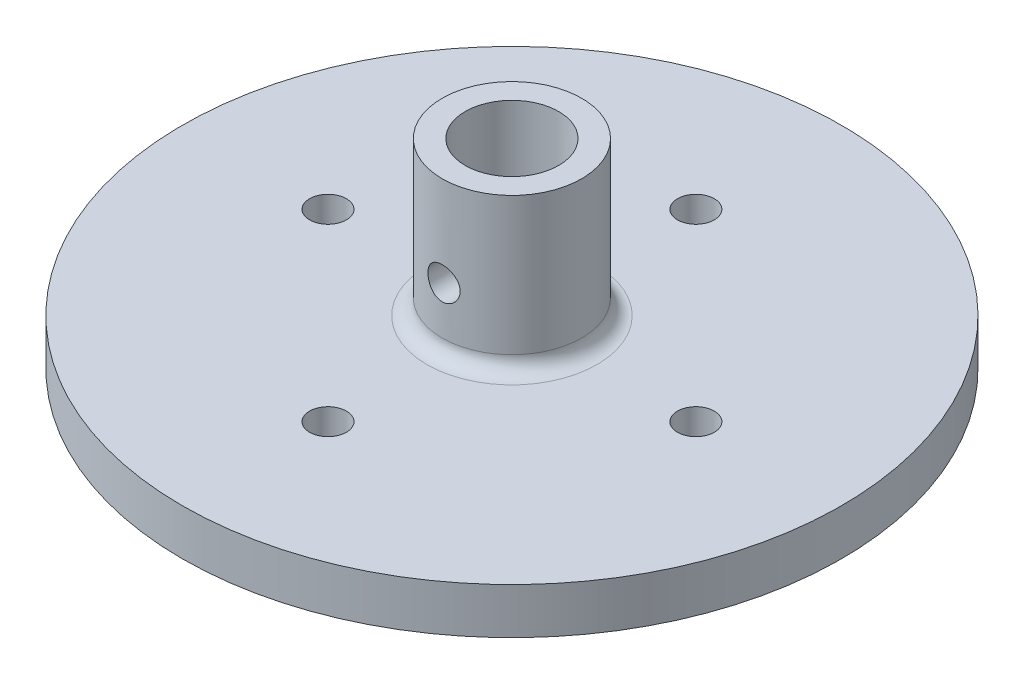
SolidWorks part; units mm, degrees
ref_plane "前视基准面" through (0, 0, 0) normal (0, 0, 1) x (1, 0, 0)
ref_plane "上视基准面" through (0, 0, 0) normal (0, 1, 0) x (1, 0, 0)
ref_plane "右视基准面" through (0, 0, 0) normal (1, 0, 0) x (0, 0, -1)
sketch "草图1" plane through (0, 0, 0) normal (0, 1, 0) x (1, 0, 0)
  circle A0 centre (0, 0) radius 21.5
  dimension "D1" = 43
extrude "凸台-拉伸1" add sketch "草图1" along normal blind 3
sketch "草图2" plane through (0, 3, 0) normal (0, 1, 0) x (1, 0, 0)
  circle A0 centre (0, 0) radius 3.05
  circle A1 centre (0, 0) radius 4.55
  dimension "D1" = 6.1
  dimension "D2" = 1.5
extrude "凸台-拉伸2" add sketch "草图2" along normal blind 10
sketch "草图3" plane through (0, 0, 0) normal (0, 0, 1) x (1, 0, 0)
  line L1 (21.5, 3) -> (-21.5, 3) construction
  circle A0 centre (0, 7.1) radius 1.05
  dimension "D1" = 2.1
  dimension "D2" = 4.1
extrude "切除-拉伸1" cut sketch "草图3" against normal mid plane 17
sketch "草图4" plane through (0, 3, 0) normal (0, 1, 0) x (1, 0, 0)
  circle A0 centre (12, 0) radius 1.2
  circle A4 centre (0, 0) radius 3.05 construction
  dimension "D1" = 2.4
  dimension "D2" = 12
extrude "切除-拉伸2" cut sketch "草图4" against normal up to next
pattern_circular "阵列(圆周)1" count 4 every 90 about axis through (0, 0, 0) along (0, 1, 0) of "切除-拉伸2"
fillet "圆角1" radius 1 1 edges at (0, 3, 4.55)
